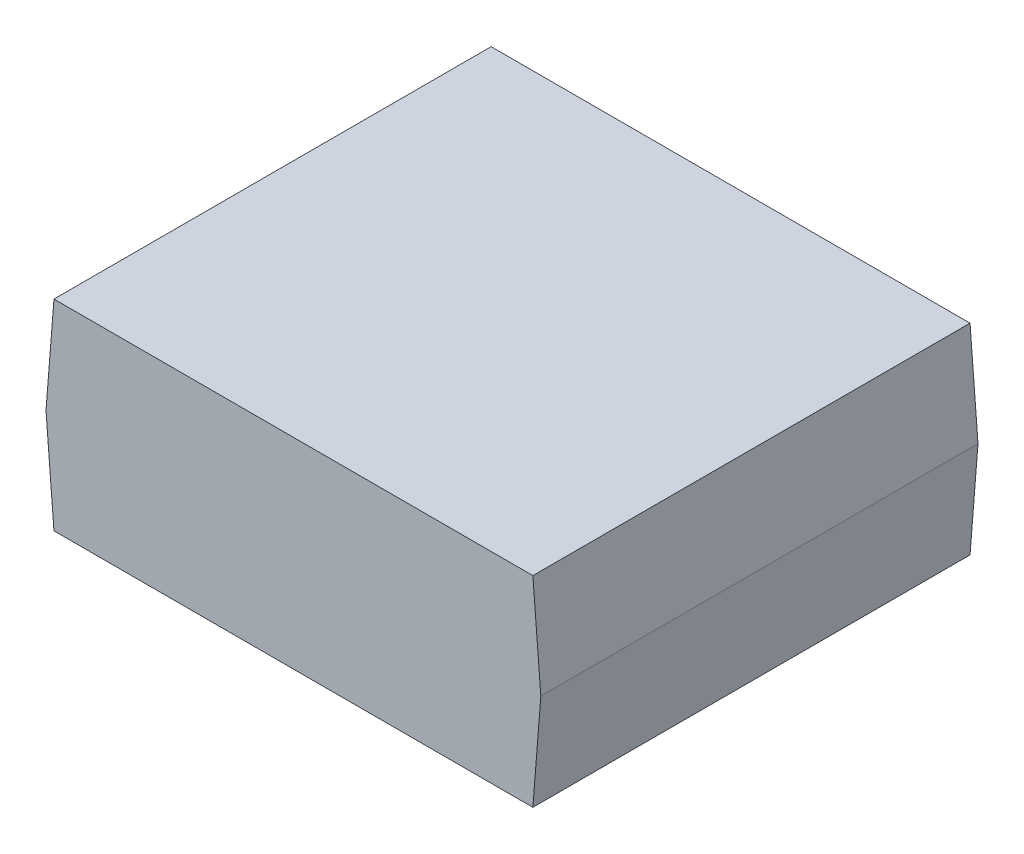
SolidWorks part; units mm, degrees
ref_plane "Front Plane" through (0, 0, 0) normal (0, 0, 1) x (1, 0, 0)
ref_plane "Top Plane" through (0, 0, 0) normal (0, 1, 0) x (1, 0, 0)
ref_plane "Right Plane" through (0, 0, 0) normal (1, 0, 0) x (0, 0, -1)
sketch "Sketch1" plane through (0, 0, 0) normal (0, 0, 1) x (1, 0, 0)
  line L0 (150.7437, -41.3892) -> (-108.45, -41.3892) construction
  line L1 (0, 0) -> (0, 10004.6633) construction
  line L2 (-120.5, 9.1108) -> (120.5, 9.1108)
  line L3 (120.5, 9.1108) -> (124.5, -41.3892)
  line L4 (-120.5, 9.1108) -> (-124.5, -41.3892)
  line L5 (120.5, -91.8892) -> (124.5, -41.3892)
  line L6 (-120.5, -91.8892) -> (120.5, -91.8892)
  line L7 (-120.5, -91.8892) -> (-124.5, -41.3892)
  point P11 (0, 9.1108)
  dimension "D1" = 120.5
  dimension "D2" = 50.5
  dimension "D3" = 124.5
extrude "Boss-Extrude1" add sketch "Sketch1" along normal blind 220
